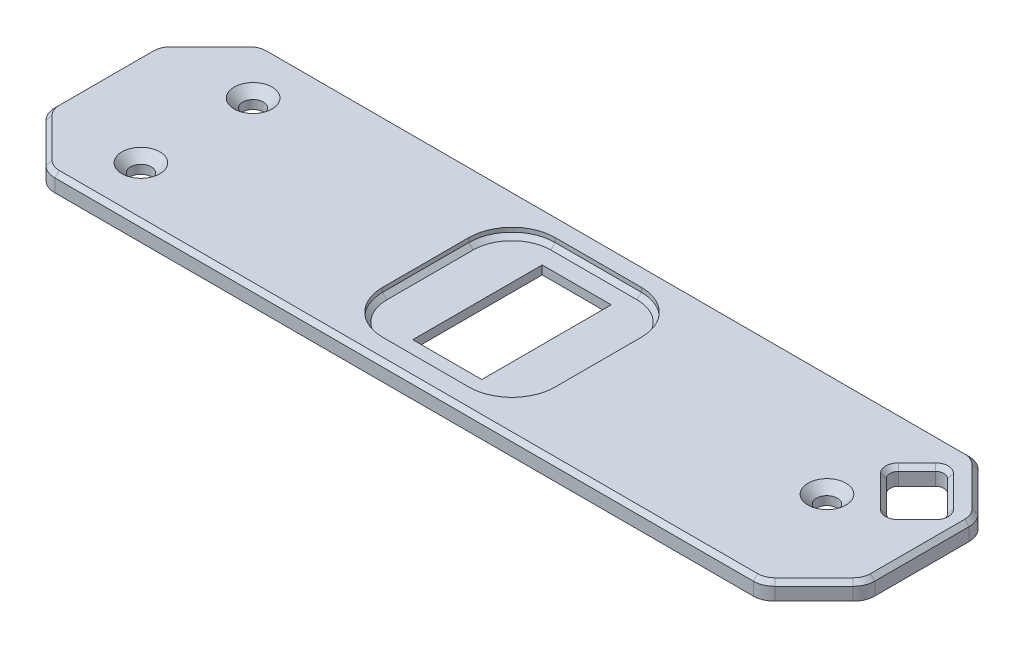
SolidWorks part; units mm, degrees
ref_plane "Front Plane" through (0, 0, 0) normal (0, 0, 1) x (1, 0, 0)
ref_plane "Top Plane" through (0, 0, 0) normal (0, 1, 0) x (1, 0, 0)
ref_plane "Right Plane" through (0, 0, 0) normal (1, 0, 0) x (0, 0, -1)
sketch "Sketch1" plane through (0, 0, 0) normal (0, 1, 0) x (1, 0, 0)
  line L0 (-47.5, 6.5) -> (-41.5, 12.5)
  line L1 (-41.5, 12.5) -> (41.5, 12.5)
  line L2 (-47.5, 6.5) -> (-47.5, -6.5)
  line L3 (-41.5, -12.5) -> (41.5, -12.5)
  line L4 (47.5, 6.5) -> (47.5, -6.5)
  line L5 (-47.5, 12.5) -> (47.5, -12.5) construction
  line L6 (-47.5, -12.5) -> (47.5, 12.5) construction
  line L7 (-47.5, -6.5) -> (-41.5, -12.5)
  line L8 (41.5, -12.5) -> (47.5, -6.5)
  line L9 (41.5, 12.5) -> (47.5, 6.5)
  point P0 (0, 0)
  dimension "D1" = 25
  dimension "D2" = 95
extrude "Boss-Extrude1" add sketch "Sketch1" along normal blind 2
fillet "Fillet1" radius 2.5 8 edges at (-41.5, 1, 12.5) (-47.5, 1, 6.5) (-47.5, 1, -6.5) (-41.5, 1, -12.5) (41.5, 1, -12.5) (47.5, 1, -6.5) (47.5, 1, 6.5) (41.5, 1, 12.5)
sketch "Sketch2" plane through (0, 2, 0) normal (0, 1, 0) x (1, 0, 0)
  line L0 (0, 12.5) -> (0, -12.5) construction
  line L1 (47.5, 0) -> (-47.5, 0) construction
  line L3 (-4, 7.5) -> (4, 7.5)
  line L4 (-4, 7.5) -> (-4, -7.5)
  line L5 (-4, -7.5) -> (4, -7.5)
  line L6 (4, 7.5) -> (4, -7.5)
  line L7 (-4, 7.5) -> (4, -7.5) construction
  line L8 (-46.7678, -7.2322) -> (-42.2322, -11.7678)
  line L9 (-40.4645, -12.5) -> (40.4645, -12.5)
  line L10 (42.2322, -11.7678) -> (46.7678, -7.2322)
  line L11 (47.5, -5.4645) -> (47.5, 5.4645)
  line L12 (46.7678, 7.2322) -> (42.2322, 11.7678)
  line L13 (40.4645, 12.5) -> (-40.4645, 12.5)
  line L14 (-42.2322, 11.7678) -> (-46.7678, 7.2322)
  line L15 (-47.5, 5.4645) -> (-47.5, -5.4645)
  line L16 (-46.7678, -7.2322) -> (-42.2322, -11.7678)
  line L17 (-40.4645, -12.5) -> (40.4645, -12.5)
  line L18 (42.2322, -11.7678) -> (46.7678, -7.2322)
  line L19 (47.5, -5.4645) -> (47.5, 5.4645)
  line L20 (46.7678, 7.2322) -> (42.2322, 11.7678)
  line L21 (40.4645, 12.5) -> (-40.4645, 12.5)
  line L22 (-42.2322, 11.7678) -> (-46.7678, 7.2322)
  line L23 (-47.5, 5.4645) -> (-47.5, -5.4645)
  line L24 (-4, -7.5) -> (4, 7.5) construction
  line L25 (-5, 10) -> (5, 10)
  line L26 (-10, 5) -> (-10, -5)
  line L27 (-5, -10) -> (5, -10)
  line L28 (10, 5) -> (10, -5)
  line L29 (-10, 10) -> (10, -10) construction
  line L30 (-10, -10) -> (10, 10) construction
  arc A0 (-10, -5) -> (-5, -10) centre (-5, -5) ccw
  arc A1 (5, -10) -> (10, -5) centre (5, -5) ccw
  arc A2 (5, 10) -> (10, 5) centre (5, 5) cw
  arc A3 (-5, 10) -> (-10, 5) centre (-5, 5) ccw
  arc A8 (-42.2322, -11.7678) -> (-40.4645, -12.5) centre (-40.4645, -10) ccw
  arc A9 (40.4645, -12.5) -> (42.2322, -11.7678) centre (40.4645, -10) ccw
  arc A10 (46.7678, -7.2322) -> (47.5, -5.4645) centre (45, -5.4645) ccw
  arc A11 (47.5, 5.4645) -> (46.7678, 7.2322) centre (45, 5.4645) ccw
  arc A12 (42.2322, 11.7678) -> (40.4645, 12.5) centre (40.4645, 10) ccw
  arc A13 (-40.4645, 12.5) -> (-42.2322, 11.7678) centre (-40.4645, 10) ccw
  arc A14 (-46.7678, 7.2322) -> (-47.5, 5.4645) centre (-45, 5.4645) ccw
  arc A15 (-47.5, -5.4645) -> (-46.7678, -7.2322) centre (-45, -5.4645) ccw
  arc A16 (-42.2322, -11.7678) -> (-40.4645, -12.5) centre (-40.4645, -10) ccw
  arc A17 (40.4645, -12.5) -> (42.2322, -11.7678) centre (40.4645, -10) ccw
  arc A18 (46.7678, -7.2322) -> (47.5, -5.4645) centre (45, -5.4645) ccw
  arc A19 (47.5, 5.4645) -> (46.7678, 7.2322) centre (45, 5.4645) ccw
  arc A20 (42.2322, 11.7678) -> (40.4645, 12.5) centre (40.4645, 10) ccw
  arc A21 (-40.4645, 12.5) -> (-42.2322, 11.7678) centre (-40.4645, 10) ccw
  arc A22 (-46.7678, 7.2322) -> (-47.5, 5.4645) centre (-45, 5.4645) ccw
  arc A23 (-47.5, -5.4645) -> (-46.7678, -7.2322) centre (-45, -5.4645) ccw
  point P22 (0, 0)
  point P30 (0, 0)
  dimension "D6" = 5
  dimension "D2" = 8
  dimension "D3" = 15
  dimension "D4" = 20
  dimension "D5" = 20
  dimension "D1" = 0
extrude "Cut-Extrude1" cut sketch "Sketch2" against normal blind 2 contours L4 L3 L6 L5
sketch "Sketch3" plane through (0, 2, 0) normal (0, 1, 0) x (1, 0, 0)
  line L0 (-5, -10) -> (5, -10) construction
  line L1 (10, 5) -> (10, -5) construction
  line L2 (-5, 10) -> (5, 10) construction
  line L3 (-10, 5) -> (-10, -5) construction
  line L4 (-5, -10) -> (5, -10)
  line L5 (10, 5) -> (10, -5)
  line L6 (-5, 10) -> (5, 10)
  line L7 (-10, 5) -> (-10, -5)
  arc A0 (-10, -5) -> (-5, -10) centre (-5, -5) ccw construction
  arc A1 (5, -10) -> (10, -5) centre (5, -5) ccw construction
  arc A2 (10, 5) -> (5, 10) centre (5, 5) ccw construction
  arc A3 (-5, 10) -> (-10, 5) centre (-5, 5) ccw construction
  arc A4 (-10, -5) -> (-5, -10) centre (-5, -5) ccw
  arc A5 (5, -10) -> (10, -5) centre (5, -5) ccw
  arc A6 (10, 5) -> (5, 10) centre (5, 5) ccw
  arc A7 (-5, 10) -> (-10, 5) centre (-5, 5) ccw
extrude "Cut-Extrude2" cut sketch "Sketch3" against normal blind 1
fillet "Fillet3" radius 0.5 8 edges at (8.5355, 1, 8.5355) (0, 1, 10) (-8.5355, 1, 8.5355) (-10, 1, 0) (-8.5355, 1, -8.5355) (0, 1, -10) (8.5355, 1, -8.5355) (10, 1, 0) profile chamfer
fillet "Fillet4" radius 0.5 16 edges at (-41.4212, 2, 12.3097) (-44.5, 2, 9.5) (-47.3097, 2, 6.4212) (-47.5, 2, 0) (-47.3097, 2, -6.4212) (-44.5, 2, -9.5) (-41.4212, 2, -12.3097) (0, 2, -12.5) (41.4212, 2, -12.3097) (44.5, 2, -9.5) (47.3097, 2, -6.4212) (47.5, 2, 0) (47.3097, 2, 6.4212) (44.5, 2, 9.5) (41.4212, 2, 12.3097) (0, 2, 12.5) profile chamfer
sketch "Sketch5" plane through (0, 2, 0) normal (0, 1, 0) x (1, 0, 0)
  line L0 (-47, 0) -> (47, 0) construction
  line L1 (-32.5, 10) -> (32.5, 10)
  line L2 (-32.5, 10) -> (-32.5, -10)
  line L3 (-32.5, -10) -> (32.5, -10)
  line L4 (32.5, 10) -> (32.5, -10)
  line L5 (-32.5, 10) -> (32.5, -10) construction
  line L6 (-32.5, -10) -> (32.5, 10) construction
  line L13 (-47, 5.4645) -> (-47, -5.4645) construction
  line L14 (47, -5.4645) -> (47, 5.4645) construction
  line L17 (41.4038, 9.0607) -> (44.9896, 5.4749)
  line L18 (39.9896, 9.0607) -> (37.8683, 6.9393)
  line L19 (44.9896, 4.0607) -> (42.8683, 1.9393)
  line L20 (37.8683, 5.5251) -> (41.4541, 1.9393)
  line L21 (46.4142, 6.8787) -> (41.8787, 11.4142) construction
  line L23 (40.4645, 12) -> (-40.4645, 12) construction
  arc A4 (42.8683, 1.9393) -> (41.4541, 1.9393) centre (42.1612, 2.6464) cw
  arc A5 (44.9896, 5.4749) -> (44.9896, 4.0607) centre (44.2825, 4.7678) cw
  arc A6 (39.9896, 9.0607) -> (41.4038, 9.0607) centre (40.6967, 8.3536) cw
  arc A7 (37.8683, 6.9393) -> (37.8683, 5.5251) centre (38.5754, 6.2322) ccw
  point P0 (0, 0)
  point P17 (38.9289, 8)
  point P20 (43.9289, 3)
  point P28 (40.6967, 9.7678)
  point P31 (37.1612, 6.2322)
  point P32 (36.5, 0)
  point P33 (-36.5, 6.5)
  point P34 (-36.5, -6.5)
  dimension "D7" = 1
  dimension "D1" = 20
  dimension "D2" = 65
  dimension "D3" = 3
  dimension "D4" = 5
  dimension "D5" = 4
  dimension "D6" = 2
  dimension "D8" = 4
  dimension "D9" = 4
  dimension "D10" = 4
extrude "Cut-Extrude3" cut sketch "Sketch5" against normal through all contours L18 A7 L20 A4 L19 A5 L17 A6
fillet "Fillet5" radius 0.5 8 edges at (37.5754, 2, -6.2322) (38.9289, 2, -8) (40.6967, 2, -9.3536) (43.1967, 2, -7.2678) (45.2825, 2, -4.7678) (43.9289, 2, -3) (42.1612, 2, -1.6464) (39.6612, 2, -3.7322) profile chamfer
hole_wizard "CSK for M2 Countersunk Flat Head Screw1" positions "3DSketch1" profile "Sketch6" countersink size "M2" standard "ISO"
sketch3d "3DSketch1"
  point P0 (36.5, 2, 0)
sketch "Sketch6" plane through (36.5, 2, 0) normal (1, 0, 0) x (0, 0, 1)
  line L0 (0, 0) -> (0, 5)
  line L1 (0, 5) -> (1.2, 4.279)
  line L2 (1.2, 4.279) -> (1.2, 1)
  line L3 (1.2, 1) -> (2.2, 0)
  line L5 (2.2, 0) -> (0, 0)
  line L6 (-1.2, 1) -> (-2.2, 0) construction
  line L10 (0, 5) -> (-1.2, 4.279) construction
  line L11 (0, -6.35) -> (0, 107.95) construction
  dimension "Hole Dia." = 2.4
  dimension "Hole Depth" = 5
  dimension "Near C'Sink Dia." = 4.4
  dimension "Near C'Sink Angle" = 90
  dimension "Drill Angle" = 118
hole_wizard "CSK for M2 Countersunk Flat Head Screw2" positions "3DSketch2" profile "Sketch7" countersink size "M2" standard "ISO"
sketch3d "3DSketch2"
  point P0 (-36.5, 2, -6.5)
  point P3 (-36.5, 2, 6.5)
sketch "Sketch7" plane through (-36.5, 2, -6.5) normal (1, 0, 0) x (0, 0, 1)
  line L0 (0, 0) -> (0, 5)
  line L1 (0, 5) -> (1.2, 4.279)
  line L2 (1.2, 4.279) -> (1.2, 1)
  line L3 (1.2, 1) -> (2.2, 0)
  line L5 (2.2, 0) -> (0, 0)
  line L6 (-1.2, 1) -> (-2.2, 0) construction
  line L10 (0, 5) -> (-1.2, 4.279) construction
  line L11 (0, -6.35) -> (0, 107.95) construction
  dimension "Hole Dia." = 2.4
  dimension "Hole Depth" = 5
  dimension "Near C'Sink Dia." = 4.4
  dimension "Near C'Sink Angle" = 90
  dimension "Drill Angle" = 118
